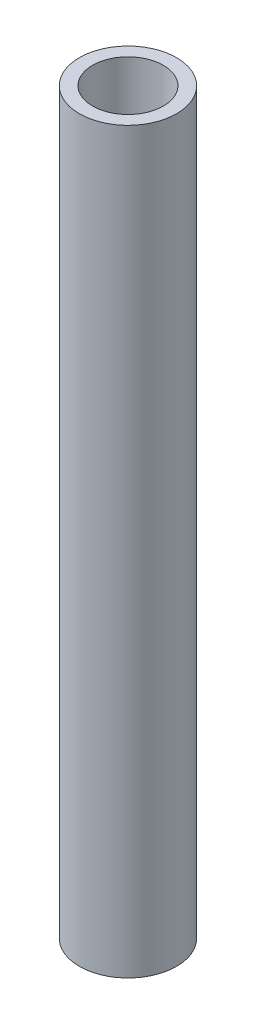
SolidWorks part; units mm, degrees
ref_plane "Front Plane" through (0, 0, 0) normal (0, 0, 1) x (1, 0, 0)
ref_plane "Top Plane" through (0, 0, 0) normal (0, 1, 0) x (1, 0, 0)
ref_plane "Right Plane" through (0, 0, 0) normal (1, 0, 0) x (0, 0, -1)
sketch "Sketch1" plane through (0, 0, 0) normal (0, 1, 0) x (1, 0, 0)
  circle A0 centre (0, 0) radius 12.1666
  circle A1 centre (0, 0) radius 16.7132
  dimension "D1" = 24.3332
  dimension "D2" = 33.4264
extrude "Boss-Extrude1" add sketch "Sketch1" along normal mid plane 254
